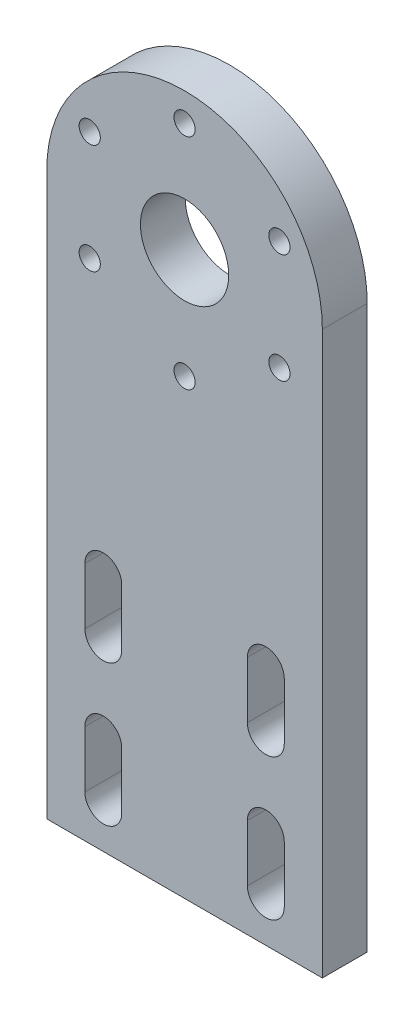
SolidWorks part; units mm, degrees
ref_plane "Front" through (0, 0, 0) normal (0, 0, 1) x (1, 0, 0)
ref_plane "Top" through (0, 0, 0) normal (0, 1, 0) x (1, 0, 0)
ref_plane "Right" through (0, 0, 0) normal (1, 0, 0) x (0, 0, -1)
sketch "Sketch1" plane through (0, 0, 0) normal (0, 0, 1) x (1, 0, 0)
  line L0 (0, -19.5) -> (0, -79.5) construction
  line L3 (19.5, 0) -> (19.5, -79.5)
  line L4 (19.5, -79.5) -> (-19.5, -79.5)
  line L5 (-19.5, 0) -> (-19.5, -79.5)
  line L6 (19.5, 0) -> (-19.5, -79.5) construction
  line L7 (19.5, -79.5) -> (-19.5, 0) construction
  arc A1 (19.5, 0) -> (-19.5, 0) centre (0, 0) ccw
  point P9 (0, -39.75)
  dimension "D2" = 39
  dimension "D3" = 60
extrude "Boss-Extrude1" add sketch "Sketch1" along normal blind 6.35
sketch "Sketch2" plane through (0, 0, 6.35) normal (0, 0, 1) x (1, 0, 0)
  line L0 (-11.5, -73.5) -> (-11.5, -65.5) construction
  line L1 (-14.11, -73.5) -> (-14.11, -65.5)
  line L2 (-8.89, -73.5) -> (-8.89, -65.5)
  line L3 (-11.5, -53.5) -> (-11.5, -45.5) construction
  line L4 (-14.11, -53.5) -> (-14.11, -45.5)
  line L5 (-8.89, -53.5) -> (-8.89, -45.5)
  line L6 (-19.5, -79.5) -> (19.5, -79.5) construction
  line L7 (-19.5, 0) -> (-19.5, -79.5) construction
  line L8 (0, -18) -> (0, -79.5) construction
  line L9 (11.5, -73.5) -> (11.5, -65.5) construction
  line L10 (14.11, -73.5) -> (14.11, -65.5)
  line L11 (8.89, -73.5) -> (8.89, -65.5)
  line L12 (11.5, -53.5) -> (11.5, -45.5) construction
  line L13 (14.11, -53.5) -> (14.11, -45.5)
  line L14 (8.89, -53.5) -> (8.89, -45.5)
  arc A0 (-14.11, -73.5) -> (-8.89, -73.5) centre (-11.5, -73.5) ccw
  arc A1 (-8.89, -65.5) -> (-14.11, -65.5) centre (-11.5, -65.5) ccw
  arc A2 (-14.11, -53.5) -> (-8.89, -53.5) centre (-11.5, -53.5) ccw
  arc A3 (-8.89, -45.5) -> (-14.11, -45.5) centre (-11.5, -45.5) ccw
  arc A5 (14.11, -73.5) -> (8.89, -73.5) centre (11.5, -73.5) cw
  arc A6 (8.89, -65.5) -> (14.11, -65.5) centre (11.5, -65.5) cw
  arc A7 (14.11, -53.5) -> (8.89, -53.5) centre (11.5, -53.5) cw
  arc A8 (8.89, -45.5) -> (14.11, -45.5) centre (11.5, -45.5) cw
  point P2 (-11.5, -69.5)
  point P7 (-11.5, -49.5)
  point P25 (11.5, -69.5)
  point P32 (11.5, -49.5)
  dimension "D4" = 5.22
  dimension "D1" = 10
  dimension "D2" = 8
  dimension "D3" = 8
  dimension "D5" = 20
extrude "Cut-Extrude1" cut sketch "Sketch2" against normal up to next
sketch "Sketch3" plane through (0, 0, 6.35) normal (0, 0, 1) x (1, 0, 0)
  circle A0 centre (0, 0) radius 6.25
  dimension "D1" = 12.5
extrude "Cut-Extrude2" cut sketch "Sketch3" against normal up to next
sketch "Sketch4" plane through (0, 0, 6.35) normal (0, 0, 1) x (1, 0, 0)
  line L0 (0, 0) -> (0, 15.5) construction
  dimension "D1" = 15.5
hole_wizard "Ø3.0mm Clearance Dowel Hole1" positions "3DSketch1" profile "Sketch5" hole size "Ø3.0" standard "ANSI Metric" end condition up to next
sketch3d "3DSketch1"
  point P0 (0, 15.5, 6.35)
sketch "Sketch5" plane through (0, 15.5, 6.35) normal (1, 0, 0) x (0, -1, 0)
  line L0 (0, 0) -> (0, 6.351)
  line L1 (0, 6.351) -> (1.5, 6.351)
  line L2 (1.5, 6.351) -> (1.5, 0)
  line L5 (1.5, 0) -> (0, 0)
  line L11 (0, -6.35) -> (0, 107.95) construction
  dimension "Thru Hole Dia." = 3
  dimension "Thru Hole Depth" = 6.351
pattern_circular "CirPattern1" count 6 over 360 about axis through (0, 0, 0) along (0, 0, 1) of "Ø3.0mm Clearance Dowel Hole1"
